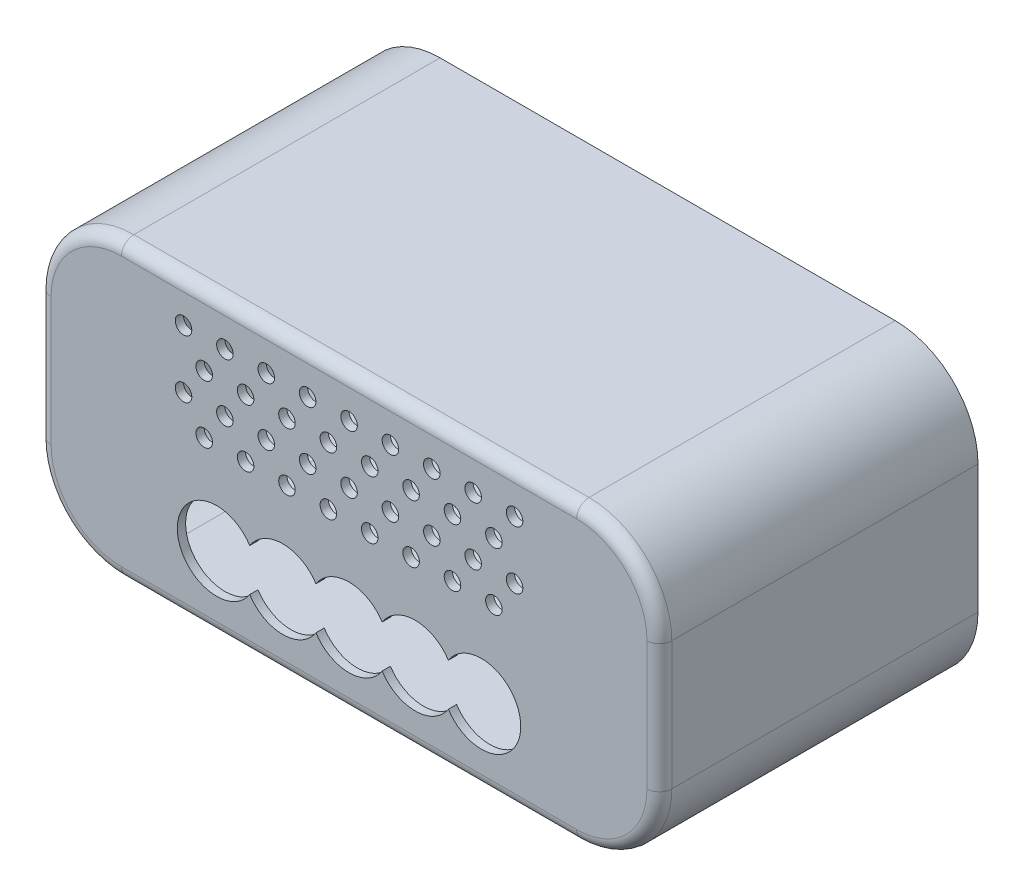
SolidWorks part; units mm, degrees
ref_plane "Front Plane" through (0, 0, 0) normal (0, 0, 1) x (1, 0, 0)
ref_plane "Top Plane" through (0, 0, 0) normal (0, 1, 0) x (1, 0, 0)
ref_plane "Right Plane" through (0, 0, 0) normal (1, 0, 0) x (0, 0, -1)
sketch "Sketch3" plane through (0, 0, -3) normal (0, 0, 1) x (1, 0, 0)
  line L0 (7.5, -48.2) -> (7.5, 5) construction
  line L1 (62.5, -66) -> (-47.5, -66)
  line L2 (82.5, -46) -> (82.5, -15)
  line L3 (62.5, 5) -> (-47.5, 5)
  line L4 (-67.5, -46) -> (-67.5, -15)
  line L5 (55, 0) -> (-55, 0) construction
  line L6 (55, -58) -> (-40, -58) construction
  line L7 (62.5, 5) -> (-47.5, 5) construction
  line L28 (-37.5, -12) -> (-27.5, -12) construction
  line L29 (-32.5, -12) -> (-32.5, -5) construction
  line L30 (-32.5, -5) -> (-22.5, -5) construction
  line L31 (-32.5, -12) -> (-32.5, -19) construction
  line L32 (-37.5, -26) -> (-27.5, -26) construction
  line L33 (-32.5, -26) -> (-32.5, -19) construction
  line L34 (-32.5, -19) -> (-22.5, -19) construction
  line L35 (2.5, -5) -> (7.5, -5) construction
  arc A0 (-47.5, -66) -> (-67.5, -46) centre (-47.5, -46) cw
  arc A1 (-47.5, 5) -> (-67.5, -15) centre (-47.5, -15) ccw
  arc A2 (82.5, -15) -> (62.5, 5) centre (62.5, -15) ccw
  arc A3 (62.5, -66) -> (82.5, -46) centre (62.5, -46) ccw
  circle A4 centre (2.5, -12) radius 2
  circle A5 centre (12.5, -12) radius 2
  circle A6 centre (39.5, -48.2) radius 9.5
  arc A7 (31.5, -53.3235) -> (31.5, -43.0765) centre (39.5, -48.2) ccw
  circle A8 centre (7.5, -48.2) radius 9.5
  circle A9 centre (23.5, -48.2) radius 9.5
  arc A10 (15.5, -53.3235) -> (31.5, -53.3235) centre (23.5, -48.2) ccw
  arc A11 (-0.5, -53.3235) -> (15.5, -53.3235) centre (7.5, -48.2) ccw
  circle A12 centre (22.5, -12) radius 2
  circle A13 centre (-8.5, -48.2) radius 9.5
  arc A14 (-16.5, -53.3235) -> (-0.5, -53.3235) centre (-8.5, -48.2) ccw
  arc A15 (-0.5, -43.0765) -> (-16.5, -43.0765) centre (-8.5, -48.2) ccw
  circle A16 centre (-24.5, -48.2) radius 9.5
  arc A17 (-16.5, -43.0765) -> (-16.5, -53.3235) centre (-24.5, -48.2) ccw
  arc A18 (15.5, -43.0765) -> (-0.5, -43.0765) centre (7.5, -48.2) ccw
  arc A19 (31.5, -43.0765) -> (15.5, -43.0765) centre (23.5, -48.2) ccw
  circle A20 centre (32.5, -12) radius 2
  circle A21 centre (42.5, -12) radius 2
  circle A23 centre (-7.5, -12) radius 2
  circle A24 centre (-17.5, -12) radius 2
  circle A25 centre (-27.5, -12) radius 2
  circle A28 centre (52.5, -12) radius 2 [skipped]
  circle A29 centre (-47.5, -12) radius 2 [skipped]
  circle A30 centre (7.5, -5) radius 2
  circle A31 centre (17.5, -5) radius 2
  circle A32 centre (27.5, -5) radius 2
  circle A33 centre (37.5, -5) radius 2
  circle A34 centre (47.5, -5) radius 2
  circle A35 centre (-2.5, -5) radius 2
  circle A36 centre (-12.5, -5) radius 2
  circle A37 centre (-22.5, -5) radius 2
  circle A38 centre (-32.5, -5) radius 2
  circle A39 centre (2.5, -26) radius 2
  circle A40 centre (12.5, -26) radius 2
  circle A41 centre (22.5, -26) radius 2
  circle A42 centre (32.5, -26) radius 2
  circle A43 centre (42.5, -26) radius 2
  circle A44 centre (-7.5, -26) radius 2
  circle A45 centre (-17.5, -26) radius 2
  circle A46 centre (-27.5, -26) radius 2
  circle A48 centre (7.5, -19) radius 2
  circle A49 centre (17.5, -19) radius 2
  circle A50 centre (27.5, -19) radius 2
  circle A51 centre (37.5, -19) radius 2
  circle A52 centre (47.5, -19) radius 2
  circle A53 centre (-2.5, -19) radius 2
  circle A54 centre (-12.5, -19) radius 2
  circle A55 centre (-22.5, -19) radius 2
  circle A56 centre (-32.5, -19) radius 2
  circle A57 centre (-37.5, -12) radius 2 [skipped]
  point P15 (-67.5, 5)
  point P18 (82.5, 5)
  dimension "D5" = 20
  dimension "D12" = 6
  dimension "D14" = 7
  dimension "D1" = 75
  dimension "D2" = 150
  dimension "D3" = 5
  dimension "D4" = 8
  dimension "D13" = 6
  dimension "D15" = 5
  dimension "D17" = 7
  dimension "D18" = 5
  dimension "D6" = 2
  dimension "D7" = 2
  dimension "D8" = 2
  dimension "D9" = 2
  dimension "D10" = 2
extrude "Boss-Extrude1" add sketch "Sketch3" against normal blind 2
sketch "Sketch5" plane through (0, 0, -5) normal (0, 0, -1) x (-1, 0, 0)
  line L0 (65.5, -46) -> (65.5, -15)
  line L1 (47.5, 3) -> (-62.5, 3)
  line L2 (-80.5, -15) -> (-80.5, -46)
  line L3 (-62.5, -64) -> (47.5, -64)
  line L4 (67.5, -46) -> (67.5, -15)
  line L5 (47.5, 5) -> (-62.5, 5)
  line L6 (-82.5, -15) -> (-82.5, -46)
  line L7 (-62.5, -66) -> (47.5, -66)
  line L8 (67.5, -46) -> (67.5, -15)
  line L9 (47.5, 5) -> (-62.5, 5)
  line L10 (-82.5, -15) -> (-82.5, -46)
  line L11 (-62.5, -66) -> (47.5, -66)
  arc A0 (65.5, -15) -> (47.5, 3) centre (47.5, -15) ccw
  arc A1 (-62.5, 3) -> (-80.5, -15) centre (-62.5, -15) ccw
  arc A2 (-80.5, -46) -> (-62.5, -64) centre (-62.5, -46) ccw
  arc A3 (47.5, -64) -> (65.5, -46) centre (47.5, -46) ccw
  arc A4 (47.5, -66) -> (67.5, -46) centre (47.5, -46) ccw
  arc A5 (67.5, -15) -> (47.5, 5) centre (47.5, -15) ccw
  arc A6 (-62.5, 5) -> (-82.5, -15) centre (-62.5, -15) ccw
  arc A7 (-82.5, -46) -> (-62.5, -66) centre (-62.5, -46) ccw
  arc A8 (47.5, -66) -> (67.5, -46) centre (47.5, -46) ccw
  arc A9 (67.5, -15) -> (47.5, 5) centre (47.5, -15) ccw
  arc A10 (-62.5, 5) -> (-82.5, -15) centre (-62.5, -15) ccw
  arc A11 (-82.5, -46) -> (-62.5, -66) centre (-62.5, -46) ccw
  dimension "D1" = 0
  dimension "D2" = 2
extrude "Boss-Extrude2" add sketch "Sketch5" along normal blind 75
fillet "Fillet1" radius 3 16 edges at (75.2279, -58.7279, -5) (80.5, -30.5, -5) (75.2279, -2.2721, -5) (7.5, 3, -5) (-60.2279, -2.2721, -5) (-65.5, -30.5, -5) (-60.2279, -58.7279, -5) (-67.5, -30.5, -3) (-61.6421, -0.8579, -3) (7.5, 5, -3) (76.6421, -0.8579, -3) (82.5, -30.5, -3) (76.6421, -60.1421, -3) (7.5, -66, -3) (7.5, -64, -5) (-61.6421, -60.1421, -3)
